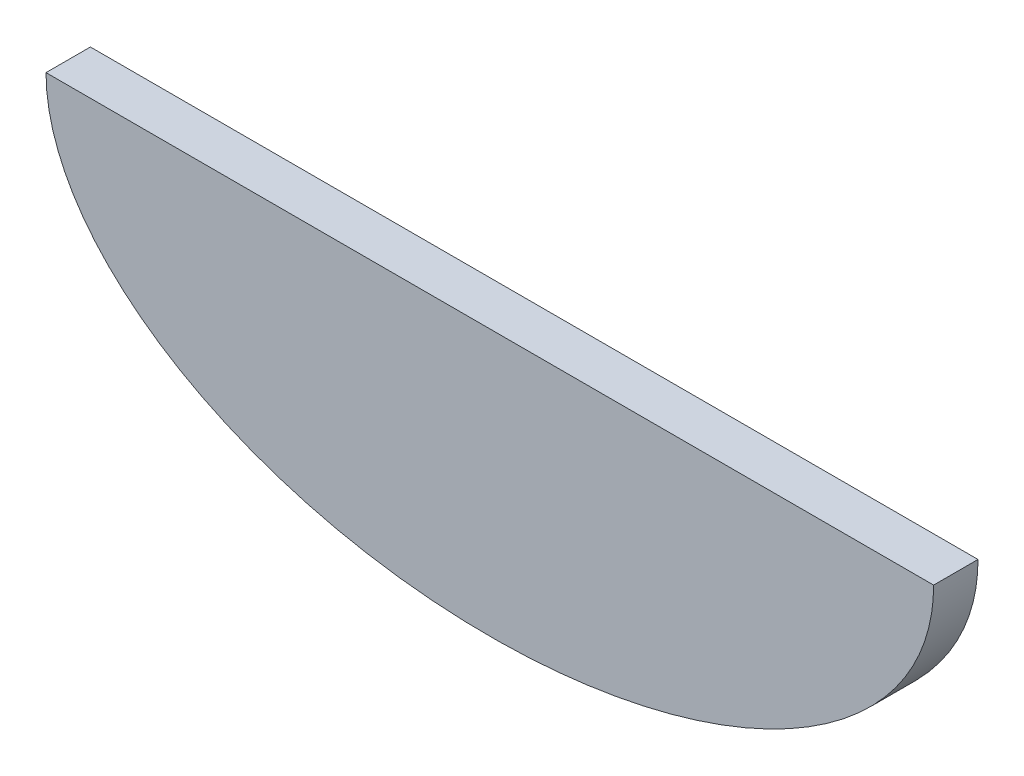
SolidWorks part; units mm, degrees
ref_plane "Alzado" through (0, 0, 0) normal (0, 0, 1) x (1, 0, 0)
ref_plane "Planta" through (0, 0, 0) normal (0, 1, 0) x (1, 0, 0)
ref_plane "Vista lateral" through (0, 0, 0) normal (1, 0, 0) x (0, 0, -1)
sketch "Croquis1" plane through (0, 0, 0) normal (0, 0, 1) x (1, 0, 0)
  line L0 (-20, 0) -> (20, 0)
  ellipse E0 centre (0, 0) end of major axis (20, 0) minor radius 12 (-20, 0) -> (20, 0) ccw
  point P1 (0, 0)
  dimension "D1" = 12
  dimension "D2" = 40
extrude "Saliente-Extruir1" add sketch "Croquis1" along normal blind 2
equation "\"6.30x2\"=6.3"
